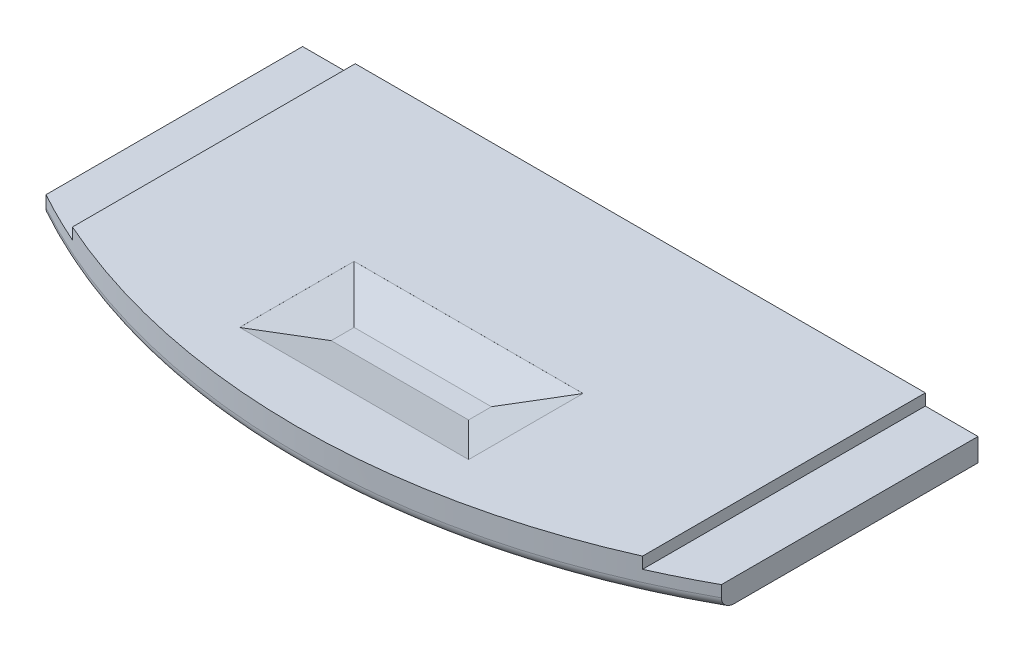
SolidWorks part; units mm, degrees
material "Plain Carbon Steel"
ref_plane "Front Plane" through (0, 0, 0) normal (0, 0, 1) x (1, 0, 0)
ref_plane "Top Plane" through (0, 0, 0) normal (0, 1, 0) x (1, 0, 0)
ref_plane "Right Plane" through (0, 0, 0) normal (1, 0, 0) x (0, 0, -1)
sketch "Sketch1" plane through (0, 0, 0) normal (0, 0, 1) x (1, 0, 0)
  line L0 (-18.7325, 0) -> (18.7325, 0)
  line L1 (18.7325, 0) -> (18.7325, 1.27)
  line L2 (18.7325, 1.27) -> (15.8115, 1.27)
  line L3 (15.8115, 1.27) -> (15.8115, 1.905)
  line L4 (15.8115, 1.905) -> (-15.8115, 1.905)
  line L5 (-15.8115, 1.905) -> (-15.8115, 1.27)
  line L6 (-15.8115, 1.27) -> (-18.7325, 1.27)
  line L7 (-18.7325, 1.27) -> (-18.7325, 0)
  point P3 (0, 0)
  dimension "D1" = 37.465
  dimension "D2" = 31.623
  dimension "D3" = 1.905
  dimension "D4" = 1.27
  dimension "D5" = 0.635
extrude "Boss-Extrude1" add sketch "Sketch1" along normal blind 19.05
sketch "Sketch2" plane through (0, 1.905, 0) normal (0, 1, 0) x (1, 0, 0)
  line L2 (15.8115, -19.05) -> (-15.8115, -19.05) construction
  line L3 (-6.35, -15.875) -> (6.35, -15.875)
  line L4 (-6.35, -15.875) -> (-6.35, -9.525)
  line L5 (-6.35, -9.525) -> (6.35, -9.525)
  line L6 (6.35, -15.875) -> (6.35, -9.525)
  line L7 (-6.35, -15.875) -> (6.35, -9.525) construction
  line L8 (-6.35, -9.525) -> (6.35, -15.875) construction
  point P0 (0, -12.7)
  point P6 (0, 0)
  dimension "D1" = 6.35
  dimension "D2" = 3.175
  dimension "D3" = 12.7
extrude "Cut-Extrude1" cut sketch "Sketch2" against normal blind 0.635
chamfer "Chamfer1" distance 2.54 angle 14 4 edges at (0, 1.27, 15.875) (-6.35, 1.27, 12.7) (0, 1.27, 9.525) (6.35, 1.27, 12.7)
sketch "Sketch3" plane through (0, 1.905, 0) normal (0, 1, 0) x (1, 0, 0)
  line L0 (-18.7325, -21.59) -> (18.7325, -21.59)
  line L1 (18.7325, -21.59) -> (18.7325, -14.2336)
  line L2 (18.7325, -19.05) -> (18.7325, 0) construction
  line L5 (-18.7325, -21.59) -> (-18.7325, -14.2336)
  line L6 (-18.7325, -19.05) -> (-18.7325, 0) construction
  line L7 (15.8115, -19.05) -> (-15.8115, -19.05) construction
  arc A0 (-18.7325, -14.2336) -> (18.7325, -14.2336) centre (0, 19.7866) ccw
  point P13 (0, -21.59)
  point P15 (-20.1281, -27.94)
  point P16 (-18.7325, -20.1609)
  point P17 (0, 0)
  dimension "D1" = 38.8366
  dimension "D2" = 2.54
extrude "Cut-Extrude2" cut sketch "Sketch3" against normal through all
fillet "Fillet1" radius 0.635 1 edges at (0, 0, 19.05)
